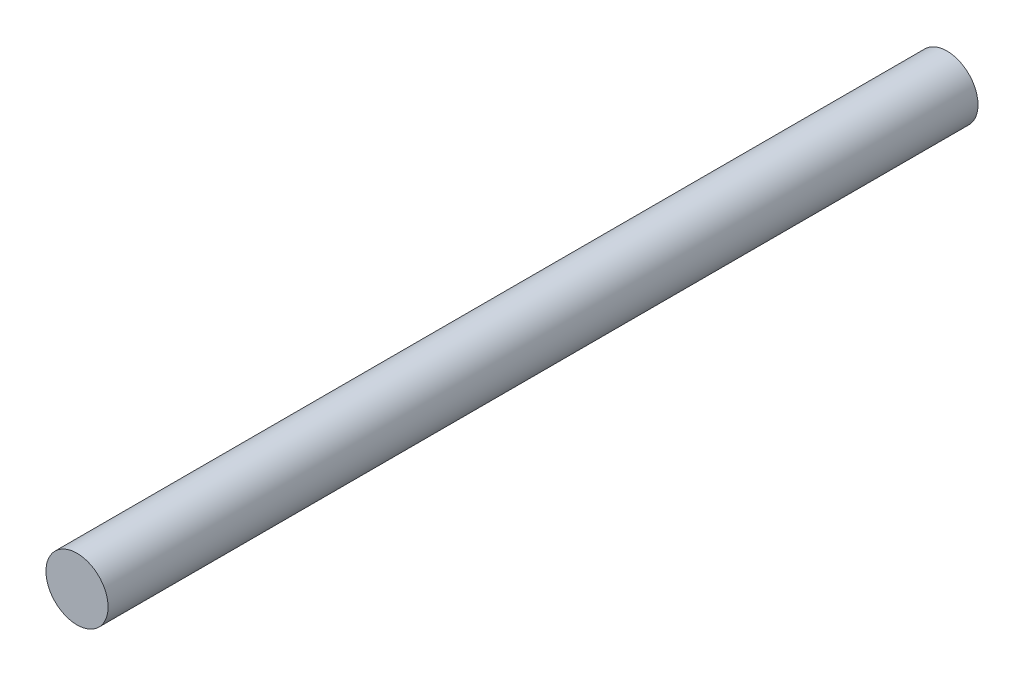
SolidWorks part; units mm, degrees
material "Alliage 1060"
ref_plane "Plan de face" through (0, 0, 0) normal (0, 0, 1) x (1, 0, 0)
ref_plane "Plan de dessus" through (0, 0, 0) normal (0, 1, 0) x (1, 0, 0)
ref_plane "Plan de droite" through (0, 0, 0) normal (1, 0, 0) x (0, 0, -1)
sketch "Esquisse1" plane through (0, 0, 0) normal (0, 0, 1) x (1, 0, 0)
  circle A0 centre (0, 0) radius 2.5
  dimension "D1" = 5
extrude "Boss.-Extru.1" add sketch "Esquisse1" against normal blind 70
